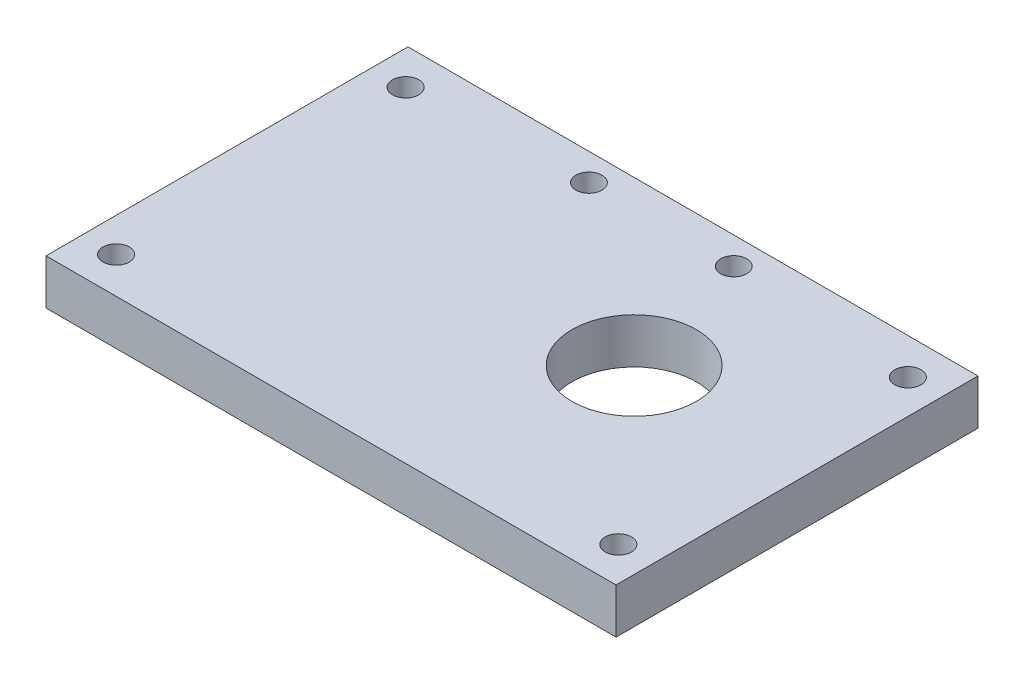
SolidWorks part; units mm, degrees
ref_plane "Front Plane" through (0, 0, 0) normal (0, 0, 1) x (1, 0, 0)
ref_plane "Top Plane" through (0, 0, 0) normal (0, 1, 0) x (1, 0, 0)
ref_plane "Right Plane" through (0, 0, 0) normal (1, 0, 0) x (0, 0, -1)
sketch "Sketch1" plane through (0, 0, 0) normal (0, 1, 0) x (1, 0, 0)
  line L1 (-40.005, 25.4) -> (40.005, 25.4)
  line L2 (-40.005, 25.4) -> (-40.005, -25.4)
  line L3 (-40.005, -25.4) -> (40.005, -25.4)
  line L4 (40.005, 25.4) -> (40.005, -25.4)
  line L5 (-40.005, 25.4) -> (40.005, -25.4) construction
  line L6 (-40.005, -25.4) -> (40.005, 25.4) construction
  point P0 (0, 0)
  dimension "D1" = 50.8
  dimension "D2" = 80.01
extrude "Boss-Extrude1" add sketch "Sketch1" along normal blind 6.35
sketch "Sketch2" plane through (0, 6.35, 0) normal (0, 1, 0) x (1, 0, 0)
  line L0 (-40.005, 25.4) -> (-40.005, -25.4) construction
  line L1 (40.005, 25.4) -> (-40.005, 25.4) construction
  line L2 (-40.005, -25.4) -> (40.005, -25.4) construction
  line L3 (40.005, -25.4) -> (40.005, 25.4) construction
  circle A0 centre (-35.2425, 20.32) radius 1.8415
  circle A1 centre (-35.2425, -20.32) radius 1.8415
  circle A2 centre (35.2425, -20.32) radius 1.8415
  circle A3 centre (35.2425, 20.32) radius 1.8415
  dimension "D3" = 3.683
  dimension "D1" = 4.7625
  dimension "D2" = 5.08
  dimension "D4" = 5.08
  dimension "D5" = 4.7625
extrude "Cut-Extrude1" cut sketch "Sketch2" against normal through all from offset 0
sketch "Sketch3" plane through (0, 6.35, 0) normal (0, 1, 0) x (1, 0, 0)
  line L0 (40.005, 25.4) -> (-40.005, 25.4) construction
  line L1 (40.005, -25.4) -> (40.005, 25.4) construction
  circle A0 centre (14.605, 2.54) radius 8.7313
  circle A1 centre (-10.795, 21.59) radius 1.8288
  circle A2 centre (9.525, 21.59) radius 1.8288
  dimension "D4" = 17.4625
  dimension "D7" = 3.6576
  dimension "D1" = 3.81
  dimension "D2" = 22.86
  dimension "D3" = 25.4
  dimension "D5" = 20.32
  dimension "D6" = 50.8
extrude "Cut-Extrude2" cut sketch "Sketch3" against normal through all contours A0 | A1 | A2
